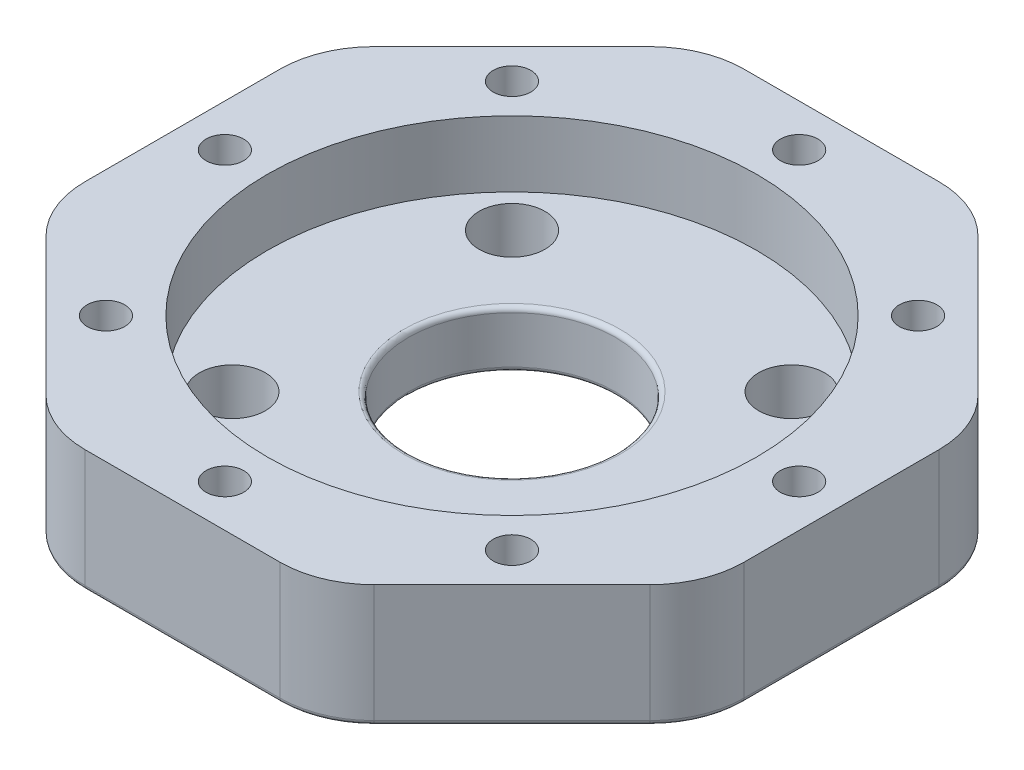
SolidWorks part; units mm, degrees
ref_plane "Front Plane" through (0, 0, 0) normal (0, 0, 1) x (1, 0, 0)
ref_plane "Top Plane" through (0, 0, 0) normal (0, 1, 0) x (1, 0, 0)
ref_plane "Right Plane" through (0, 0, 0) normal (1, 0, 0) x (0, 0, -1)
sketch "Sketch1" plane through (0, 0, 0) normal (0, 1, 0) x (1, 0, 0)
  line L0 (0, 0) -> (-30763.4145, 0) construction
  line L1 (0, 0) -> (0, -30763.4145) construction
  circle A0 centre (0, 0) radius 32
  dimension "D1" = 64
extrude "Boss-Extrude1" add sketch "Sketch1" along normal blind 13
sketch "Sketch2" plane through (0, 13, 0) normal (0, 1, 0) x (1, 0, 0)
  line L0 (0, 0) -> (-50000, 0) construction
  line L1 (0, 0) -> (0, -50000) construction
  circle A0 centre (0, 0) radius 27
  dimension "D1" = 54
extrude "Cut-Extrude1" cut sketch "Sketch2" against normal offset from surface (7 mm away) 6 up to face at (0, 0, 32)
sketch "Sketch3" plane through (0, 6, 0) normal (0, 1, 0) x (1, 0, 0)
  line L0 (0, 0) -> (-50000, 0) construction
  line L1 (0, 0) -> (0, -50000) construction
  line L2 (0, 0) -> (-35355.3391, 35355.3391) construction
  circle A0 centre (0, 0) radius 21 construction
  circle A1 centre (-14.8492, 14.8492) radius 2.5
  circle A2 centre (14.8492, 14.8492) radius 2.5
  circle A3 centre (14.8492, -14.8492) radius 2.5
  circle A4 centre (-14.8492, -14.8492) radius 2.5
  point P20 (0, 0)
  dimension "D1" = 42
  dimension "D3" = 5
  dimension "D2" = 45
  dimension "D4" = 4
extrude "Cut-Extrude2" cut sketch "Sketch3" against normal through all
sketch "Sketch4" plane through (0, 6, 0) normal (0, 1, 0) x (1, 0, 0)
  line L0 (0, 0) -> (-50000, 0) construction
  line L1 (0, 0) -> (0, -50000) construction
  line L2 (0, 0) -> (-35355.3391, 35355.3391) construction
  circle A0 centre (0, 0) radius 21 construction
  circle A1 centre (-14.8492, 14.8492) radius 3.5
  circle A2 centre (14.8492, 14.8492) radius 3.5
  circle A3 centre (14.8492, -14.8492) radius 3.5
  circle A4 centre (-14.8492, -14.8492) radius 3.5
  point P21 (0, 0)
  dimension "D1" = 42
  dimension "D3" = 7
  dimension "D2" = 45
  dimension "D4" = 4
extrude "Cut-Extrude3" cut sketch "Sketch4" against normal blind 5
sketch "Sketch7" plane through (0, 6, 0) normal (0, 1, 0) x (1, 0, 0)
  line L0 (0, 0) -> (-50000, 0) construction
  line L1 (0, 0) -> (0, -50000) construction
  circle A0 centre (0, 0) radius 27
  circle A1 centre (0, 0) radius 26
  dimension "D1" = 54
  dimension "D2" = 52
extrude "Boss-Extrude2" add sketch "Sketch7" along normal up to surface (7 mm away) up to face at (0, 13, 27)
sketch "Sketch8" plane through (0, 6, 0) normal (0, 1, 0) x (1, 0, 0)
  line L0 (0, 0) -> (-50000, 0) construction
  line L1 (0, 0) -> (0, -50000) construction
  circle A0 centre (0, 0) radius 11
  dimension "D1" = 22
extrude "Cut-Extrude6" cut sketch "Sketch8" against normal through all
sketch "Sketch10" plane through (0, 0, 0) normal (0, 1, 0) x (1, 0, 0)
  line L0 (0, 0) -> (-50000, 0) construction
  line L1 (0, 0) -> (0, -50000) construction
  line L10 (10.3553, 35) -> (-10.3553, 35)
  line L11 (-17.4264, 32.0711) -> (-32.0711, 17.4264)
  line L12 (-35, 10.3553) -> (-35, -10.3553)
  line L13 (35, 10.3553) -> (35, -10.3553)
  line L14 (17.4264, 32.0711) -> (32.0711, 17.4264)
  line L15 (17.4264, -32.0711) -> (32.0711, -17.4264)
  line L16 (-17.4264, -32.0711) -> (-32.0711, -17.4264)
  line L17 (10.3553, -35) -> (-10.3553, -35)
  circle A10 centre (0, 0) radius 32 construction
  circle A11 centre (0, 0) radius 32
  circle A12 centre (0, 0) radius 35 construction
  arc A13 (-17.4264, -32.0711) -> (-10.3553, -35) centre (-10.3553, -25) ccw
  arc A14 (-32.0711, -17.4264) -> (-35, -10.3553) centre (-25, -10.3553) cw
  arc A15 (-32.0711, 17.4264) -> (-35, 10.3553) centre (-25, 10.3553) ccw
  arc A16 (17.4264, -32.0711) -> (10.3553, -35) centre (10.3553, -25) cw
  arc A17 (32.0711, -17.4264) -> (35, -10.3553) centre (25, -10.3553) ccw
  arc A18 (35, 10.3553) -> (32.0711, 17.4264) centre (25, 10.3553) ccw
  arc A19 (17.4264, 32.0711) -> (10.3553, 35) centre (10.3553, 25) ccw
  arc A20 (-10.3553, 35) -> (-17.4264, 32.0711) centre (-10.3553, 25) ccw
  point P9 (0, -35)
  point P16 (0, 35)
  point P19 (35, 0)
  point P20 (-35, 0)
  point P23 (-14.4975, -35)
  point P26 (-35, -14.4975)
  point P29 (-35, 14.4975)
  point P32 (14.4975, -35)
  point P35 (35, -14.4975)
  point P38 (35, 14.4975)
  point P41 (14.4975, 35)
  point P44 (-14.4975, 35)
  dimension "D1" = 70
  dimension "D2" = 10
fillet "Fillet2" radius 0.5 2 edges at (0, 0, 11) (0, 6, 11)
extrude "Boss-Extrude3" add sketch "Sketch10" along normal blind 13
sketch "Sketch11" plane through (0, 13, 0) normal (0, 1, 0) x (1, 0, 0)
  line L0 (0, 0) -> (-50000, 0) construction
  line L1 (0, 0) -> (0, -50000) construction
  line L2 (0, 0) -> (-35355.3391, 35355.3391) construction
  line L3 (-17.4264, 32.0711) -> (-32.0711, 17.4264) construction
  circle A0 centre (0, 0) radius 30.5 construction
  circle A9 centre (-21.5668, 21.5668) radius 2
  circle A10 centre (21.5668, 21.5668) radius 2
  circle A11 centre (21.5668, -21.5668) radius 2
  circle A12 centre (-21.5668, -21.5668) radius 2
  point P20 (0, 0)
  dimension "D1" = 4.5
  dimension "D2" = 4
extrude "Cut-Extrude9" cut sketch "Sketch11" against normal through all
fillet "Fillet3" radius 0.5 16 edges at (14.1822, 0, 34.2388) (0, 0, 35) (-14.1822, 0, 34.2388) (-24.7487, 0, 24.7487) (-34.2388, 0, 14.1822) (-35, 0, 0) (-34.2388, 0, -14.1822) (-24.7487, 0, -24.7487) (-14.1822, 0, -34.2388) (0, 0, -35) (14.1822, 0, -34.2388) (24.7487, 0, -24.7487) (34.2388, 0, -14.1822) (35, 0, 0) (34.2388, 0, 14.1822) (24.7487, 0, 24.7487)
sketch "Sketch5" plane through (0, 13, 0) normal (0, 1, 0) x (1, 0, 0)
  line L0 (0, 0) -> (-50000, 0) construction
  line L1 (0, 0) -> (0, -50000) construction
  circle A0 centre (0, 0) radius 30.5 construction
  circle A1 centre (0, 30.5) radius 2
  circle A2 centre (30.5, 0) radius 2
  circle A3 centre (0, -30.5) radius 2
  circle A4 centre (-30.5, 0) radius 2
  point P18 (0, 0)
  dimension "D1" = 61
  dimension "D2" = 4
  dimension "D3" = 4
extrude "Cut-Extrude11" cut sketch "Sketch5" against normal through all
sketch "Sketch12" plane through (0, 0, 0) normal (0, -1, 0) x (1, 0, 0)
  line L0 (0, 0) -> (-50000, 0) construction
  line L1 (0, 0) -> (0, -50000) construction
  line L2 (-3.1754, 30.5) -> (-1.5877, 27.75)
  line L3 (-30.5, -3.1754) -> (-27.75, -1.5877)
  line L4 (-27.75, -1.5877) -> (-27.75, 1.5877)
  line L5 (-27.75, 1.5877) -> (-30.5, 3.1754)
  line L6 (-30.5, 3.1754) -> (-33.25, 1.5877)
  line L7 (-33.25, 1.5877) -> (-33.25, -1.5877)
  line L8 (-33.25, -1.5877) -> (-30.5, -3.1754)
  line L9 (-1.5877, 27.75) -> (1.5877, 27.75)
  line L10 (1.5877, 27.75) -> (3.1754, 30.5)
  line L11 (3.1754, 30.5) -> (1.5877, 33.25)
  line L12 (1.5877, 33.25) -> (-1.5877, 33.25)
  line L13 (-1.5877, 33.25) -> (-3.1754, 30.5)
  line L14 (30.5, 3.1754) -> (27.75, 1.5877)
  line L15 (27.75, 1.5877) -> (27.75, -1.5877)
  line L16 (27.75, -1.5877) -> (30.5, -3.1754)
  line L17 (30.5, -3.1754) -> (33.25, -1.5877)
  line L18 (33.25, -1.5877) -> (33.25, 1.5877)
  line L19 (33.25, 1.5877) -> (30.5, 3.1754)
  line L20 (3.1754, -30.5) -> (1.5877, -27.75)
  line L21 (1.5877, -27.75) -> (-1.5877, -27.75)
  line L22 (-1.5877, -27.75) -> (-3.1754, -30.5)
  line L23 (-3.1754, -30.5) -> (-1.5877, -33.25)
  line L24 (-1.5877, -33.25) -> (1.5877, -33.25)
  line L25 (1.5877, -33.25) -> (3.1754, -30.5)
  circle A0 centre (-30.5, 0) radius 2.75 construction
  circle A1 centre (0, 30.5) radius 2.75 construction
  circle A2 centre (30.5, 0) radius 2.75 construction
  circle A3 centre (0, -30.5) radius 2.75 construction
  point P41 (0, 0)
  dimension "D1" = 5.5
extrude "Cut-Extrude12" cut sketch "Sketch12" against normal blind 3
